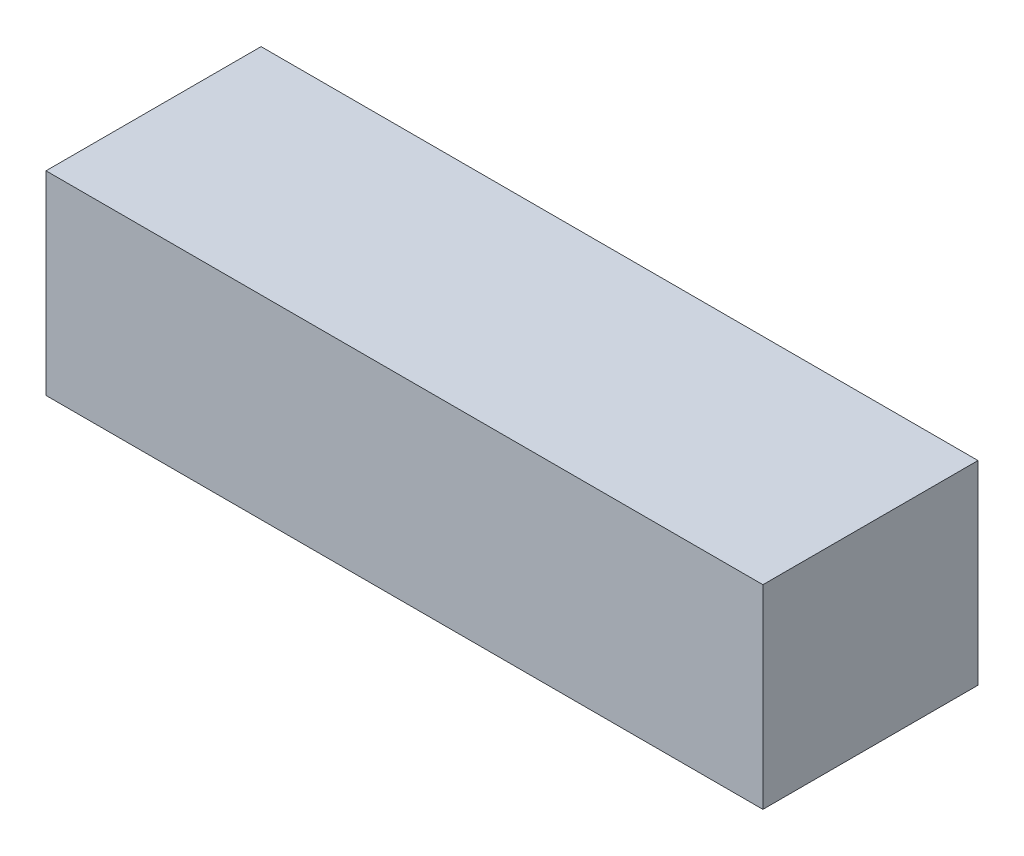
SolidWorks part; units mm, degrees
ref_plane "Front Plane" through (0, 0, 0) normal (0, 0, 1) x (1, 0, 0)
ref_plane "Top Plane" through (0, 0, 0) normal (0, 1, 0) x (1, 0, 0)
ref_plane "Right Plane" through (0, 0, 0) normal (1, 0, 0) x (0, 0, -1)
sketch "Sketch1" plane through (0, 0, 0) normal (0, 1, 0) x (1, 0, 0)
  line L1 (-70, -21) -> (70, -21)
  line L2 (-70, -21) -> (-70, 21)
  line L3 (-70, 21) -> (70, 21)
  line L4 (70, -21) -> (70, 21)
  line L5 (-70, -21) -> (70, 21) construction
  line L6 (-70, 21) -> (70, -21) construction
  point P0 (0, 0)
  dimension "D1" = 140
  dimension "D2" = 42
extrude "Boss-Extrude1" add sketch "Sketch1" along normal blind 38
